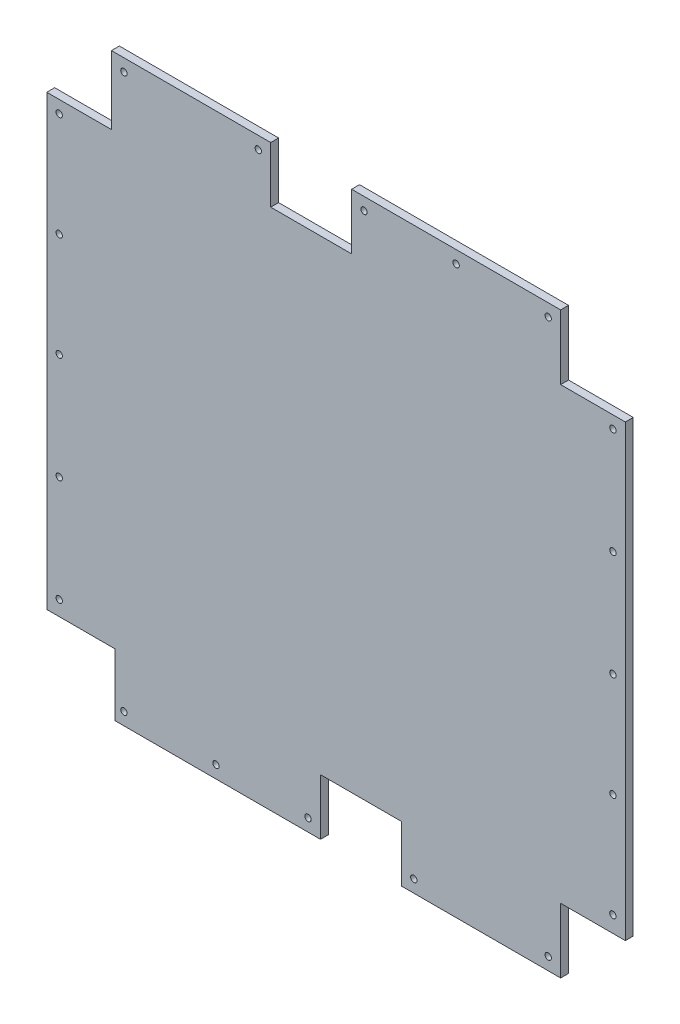
SolidWorks part; units mm, degrees
material "Acrylic (Medium-high impact)"
ref_plane "Front Plane" through (0, 0, 0) normal (0, 0, 1) x (1, 0, 0)
ref_plane "Top Plane" through (0, 0, 0) normal (0, 1, 0) x (1, 0, 0)
ref_plane "Right Plane" through (0, 0, 0) normal (1, 0, 0) x (0, 0, -1)
sketch "Sketch1" plane through (0, 0, 0) normal (0, 0, 1) x (1, 0, 0)
  line L0 (12.5, 232.5) -> (180.5, 232.5)
  line L1 (-177.5, -232.5) -> (-12.5, -232.5)
  line L2 (-232.5, -182.5) -> (-232.5, 177.5)
  line L3 (-180.5, 232.5) -> (-52.5, 232.5)
  line L4 (232.5, -180.5) -> (232.5, 180.5)
  line L5 (52.5, -232.5) -> (180.5, -232.5)
  line L6 (-232.5, 0) -> (232.5, 0) construction
  line L7 (22.5, 222.5) -> (170.5, 222.5) construction
  line L8 (222.5, 170.5) -> (222.5, 0) construction
  line L9 (-232.5, 177.5) -> (-180.5, 177.5)
  line L10 (-180.5, 232.5) -> (-180.5, 177.5)
  line L11 (-222.5, 167.5) -> (-222.5, 0) construction
  line L12 (-52.5, 232.5) -> (-52.5, 187.5)
  line L13 (-52.5, 187.5) -> (12.5, 187.5)
  line L14 (12.5, 232.5) -> (12.5, 187.5)
  line L17 (232.5, 180.5) -> (180.5, 180.5)
  line L18 (180.5, 232.5) -> (180.5, 180.5)
  line L21 (232.5, -180.5) -> (180.5, -180.5)
  line L22 (180.5, -232.5) -> (180.5, -180.5)
  line L24 (52.5, -232.5) -> (52.5, -187.5)
  line L25 (52.5, -187.5) -> (-12.5, -187.5)
  line L26 (-12.5, -232.5) -> (-12.5, -187.5)
  line L29 (-232.5, -182.5) -> (-177.5, -182.5)
  line L30 (-177.5, -232.5) -> (-177.5, -182.5)
  circle A0 centre (222.5, 170.5) radius 2.55
  circle A1 centre (170.5, 222.5) radius 2.55
  circle A2 centre (22.5, 222.5) radius 2.55
  circle A3 centre (96.5, 222.5) radius 2.55
  circle A4 centre (-170.5, 222.5) radius 2.55
  circle A5 centre (-62.5, 222.5) radius 2.55
  circle A6 centre (-222.5, 167.5) radius 2.55
  circle A7 centre (222.5, 0) radius 2.55
  circle A8 centre (222.5, 85.25) radius 2.55
  circle A9 centre (-222.5, 0) radius 2.55
  circle A10 centre (-222.5, 83.75) radius 2.55
  circle A11 centre (222.5, -83.75) radius 2.55
  circle A12 centre (222.5, -167.5) radius 2.55
  circle A13 centre (170.5, -222.5) radius 2.55
  circle A14 centre (62.5, -222.5) radius 2.55
  circle A15 centre (-22.5, -222.5) radius 2.55
  circle A16 centre (-96.5, -222.5) radius 2.55
  circle A17 centre (-170.5, -222.5) radius 2.55
  circle A18 centre (-222.5, -170.5) radius 2.55
  circle A19 centre (-222.5, -85.25) radius 2.55
  point P0 (0, 0)
  point P3 (0, 0)
  point P68 (0, 0)
  dimension "D21" = 5.1
  dimension "D22" = 10
  dimension "D23" = 10
  dimension "D24" = 5.1
  dimension "D25" = 10
  dimension "D26" = 10
  dimension "D27" = 5.1
  dimension "D28" = 10
  dimension "D29" = 10
  dimension "D30" = 5.1
  dimension "D31" = 5.1
  dimension "D32" = 10
  dimension "D33" = 10
  dimension "D34" = 5.1
  dimension "D35" = 10
  dimension "D36" = 10
  dimension "D37" = 5.1
  dimension "D38" = 10
  dimension "D39" = 10
  dimension "D40" = 5.1
  dimension "D41" = 10
  dimension "D42" = 5.1
  dimension "D43" = 5.1
  dimension "D44" = 10
  dimension "D45" = 5.1
  dimension "D2" = 232.5
  dimension "D3" = 52
  dimension "D4" = 52
  dimension "D5" = 65
  dimension "D6" = 45
  dimension "D7" = 168
  dimension "D8" = 128
  dimension "D9" = 465
  dimension "D10" = 52
  dimension "D11" = 55
  dimension "D12" = 50
  dimension "D13" = 165
  dimension "D14" = 128
  dimension "D15" = 65
  dimension "D16" = 45
  dimension "D17" = 52
  dimension "D18" = 52
  dimension "D19" = 55
  dimension "D20" = 465
  dimension "D46" = 2
extrude "Boss-Extrude1" add sketch "Sketch1" along normal blind 6.35
equation "\"D2@Sketch1\"=\"D9@Sketch1\"/2"
